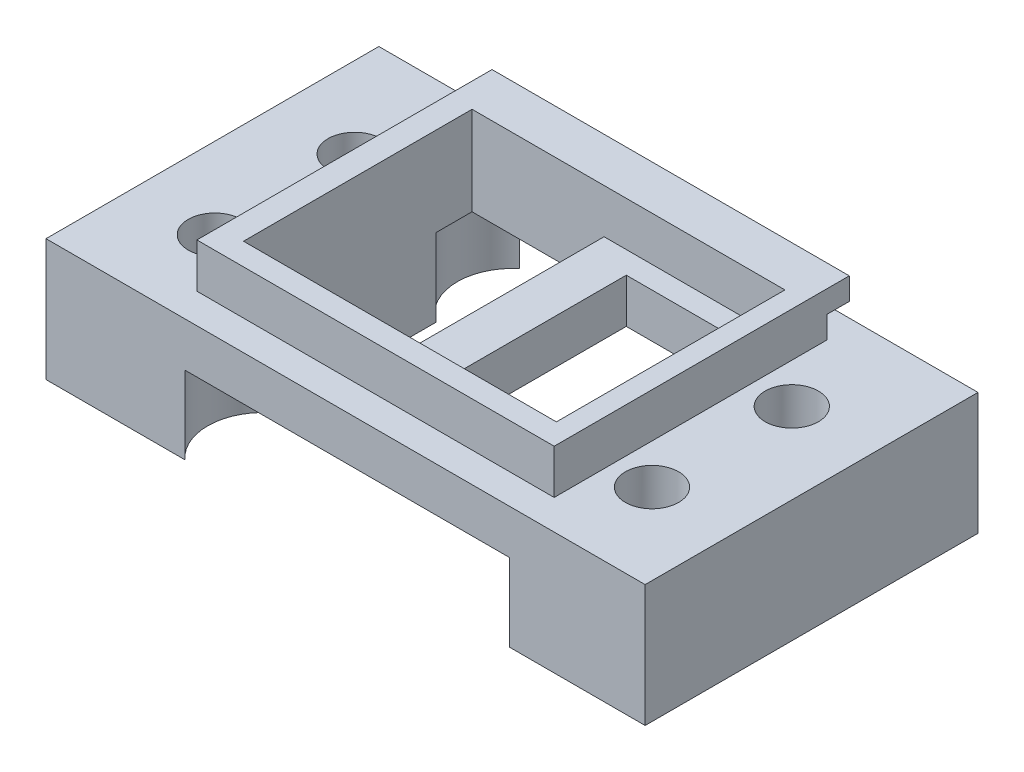
SolidWorks part; units mm, degrees
ref_plane "Front Plane" through (0, 0, 0) normal (0, 0, 1) x (1, 0, 0)
ref_plane "Top Plane" through (0, 0, 0) normal (0, 1, 0) x (1, 0, 0)
ref_plane "Right Plane" through (0, 0, 0) normal (1, 0, 0) x (0, 0, -1)
sketch "Sketch2" plane through (0, 0, 0) normal (0, 1, 0) x (1, 0, 0)
  line L1 (-9.385, 4.8519) -> (10.615, 4.8519)
  line L2 (-9.385, 4.8519) -> (-9.385, -10.1481)
  line L3 (-9.385, -10.1481) -> (10.615, -10.1481)
  line L4 (10.615, 4.8519) -> (10.615, -10.1481)
  dimension "D1" = 20
  dimension "D2" = 15
extrude "Boss-Extrude1" add sketch "Sketch2" along normal blind 2
sketch "Sketch3" plane through (0, 2, 0) normal (0, 1, 0) x (1, 0, 0)
  line L0 (-9.385, 4.8519) -> (-9.385, -10.1481) construction
  line L1 (-6.335, 2.5019) -> (7.765, 2.5019)
  line L2 (-6.335, 2.5019) -> (-6.335, -7.7981)
  line L3 (-6.335, -7.7981) -> (7.765, -7.7981)
  line L4 (7.765, 2.5019) -> (7.765, -7.7981)
  line L5 (-7.435, 3.5019) -> (8.665, 3.5019)
  line L6 (-7.435, 3.5019) -> (-7.435, -8.7981)
  line L7 (-7.435, -8.7981) -> (8.665, -8.7981)
  line L8 (8.665, 3.5019) -> (8.665, -8.7981)
  line L9 (10.615, 4.8519) -> (-9.385, 4.8519) construction
  dimension "D1" = 10.3
  dimension "D2" = 12.3
  dimension "D3" = 14.1
  dimension "D4" = 16.1
  dimension "D5" = 1.95
  dimension "D6" = 3.05
  dimension "D7" = 1.35
  dimension "D8" = 2.35
extrude "Boss-Extrude2" add sketch "Sketch3" along normal blind 2
sketch "Sketch4" plane through (0, 2, 0) normal (0, 1, 0) x (1, 0, 0)
  line L0 (0.615, 4.8519) -> (0.615, -10.1481) construction
  line L1 (10.615, 4.8519) -> (-9.385, 4.8519) construction
  line L2 (-9.385, -10.1481) -> (10.615, -10.1481) construction
  line L3 (-9.385, -2.6481) -> (10.615, -2.6481) construction
  line L4 (-9.385, 4.8519) -> (-9.385, -10.1481) construction
  line L5 (10.615, -10.1481) -> (10.615, 4.8519) construction
  line L6 (-4.385, -6.6602) -> (-4.385, 1.5019) construction
  line L7 (-6.335, -6.7981) -> (-6.335, 2.5019)
  line L8 (-0.385, -6.7981) -> (-0.385, 2.5019)
  line L9 (5.615, -6.6602) -> (5.615, 1.364) construction
  line L12 (7.765, -7.7981) -> (7.765, 1.5019)
  line L13 (1.615, -7.7981) -> (1.615, 1.5019)
  line L14 (-6.335, 2.5019) -> (-0.385, 2.5019)
  line L15 (-6.335, -6.7981) -> (-0.385, -6.7981)
  line L16 (1.615, 1.5019) -> (7.765, 1.5019)
  line L17 (1.615, -7.7981) -> (7.765, -7.7981)
  line L18 (-6.335, 2.5019) -> (-6.335, -7.7981) construction
  line L19 (7.765, -7.7981) -> (7.765, 2.5019) construction
  line L20 (7.765, 2.5019) -> (-6.335, 2.5019) construction
  line L21 (-6.335, -7.7981) -> (7.765, -7.7981) construction
  line L22 (-6.335, -7.7981) -> (7.765, -7.7981) construction
  line L23 (7.765, 2.5019) -> (-6.335, 2.5019) construction
  point P14 (-4.385, -2.6481)
  point P21 (5.615, -2.6481)
  dimension "D1" = 5
  dimension "D2" = 1
  dimension "D3" = 0
  dimension "D4" = 1
  dimension "D5" = 0
  dimension "D6" = 1
  dimension "D7" = 1
  dimension "D8" = 0
  dimension "D9" = 1
  dimension "D10" = 0
extrude "Cut-Extrude1" cut sketch "Sketch4" against normal blind 2
sketch "Sketch5" plane through (0, 2, 0) normal (0, 1, 0) x (1, 0, 0)
  line L1 (-6.335, -6.7981) -> (-6.335, -7.7981) construction
  line L2 (8.665, -8.7981) -> (8.665, 3.5019) construction
  line L3 (-2.36, 2.5019) -> (-2.36, -7.7981) construction
  line L5 (-6.335, -7.7981) -> (1.615, -7.7981) construction
  line L10 (-6.335, -3.4481) -> (8.665, -3.4481) construction
  dimension "D3" = 4.35
sketch "Sketch7" plane through (0, 0, -3.5019) normal (0, 0, -1) x (-1, 0, 0)
  line L0 (7.435, 4) -> (7.435, 2) construction
  line L1 (-8.665, 4) -> (7.435, 4)
  line L2 (-8.665, 4) -> (-8.665, 3)
  line L3 (-8.665, 3) -> (7.435, 3)
  line L4 (7.435, 4) -> (7.435, 3)
  dimension "D1" = 1
extrude "Boss-Extrude3" add sketch "Sketch7" along normal blind 1
sketch "Sketch8" plane through (0, 0, 0) normal (0, -1, 0) x (-1, 0, 0)
  line L0 (9.385, -10.1481) -> (-10.615, -10.1481) construction
  line L1 (0.385, -10.1481) -> (-1.615, -10.1481)
  line L2 (0.385, -10.1481) -> (0.385, 4.8519)
  line L3 (0.385, 4.8519) -> (-1.615, 4.8519)
  line L4 (-1.615, -10.1481) -> (-1.615, 4.8519)
  line L5 (-10.615, 4.8519) -> (9.385, 4.8519) construction
extrude "Boss-Extrude4" add sketch "Sketch8" along normal blind 30
sketch "Sketch9" plane through (1.615, 0, 0) normal (1, 0, 0) x (0, 0, -1)
  line L0 (-2.6481, 0) -> (-2.6481, -30) construction
  line L1 (-10.1481, 0) -> (4.8519, 0) construction
  line L2 (4.8519, -30) -> (-10.1481, -30) construction
  line L3 (-2.6481, -27) -> (-2.6481, -3) construction
  line L6 (-4.4481, -27) -> (-4.4481, -3)
  line L7 (-0.8481, -27) -> (-0.8481, -3)
  arc A2 (-4.4481, -27) -> (-0.8481, -27) centre (-2.6481, -27) ccw
  arc A3 (-0.8481, -3) -> (-4.4481, -3) centre (-2.6481, -3) ccw
  point P8 (-2.6481, -15)
  dimension "D1" = 3
  dimension "D2" = 1.8
extrude "Cut-Extrude2" cut sketch "Sketch9" against normal blind 20
ref_plane "Plane1" through (0, 0, 3.0391) normal (0, 0, -1) x (-1, 0, 0)
sketch "Sketch11" plane through (0, 0, 0) normal (0, -1, 0) x (1, 0, 0)
  line L8 (-0.385, -4.8519) -> (-9.385, -4.8519) construction
  line L9 (-9.385, 10.1481) -> (-12.885, 10.1481)
  line L10 (-9.385, 10.1481) -> (-9.385, -4.8519)
  line L11 (-9.385, -4.8519) -> (-12.885, -4.8519)
  line L12 (-12.885, 10.1481) -> (-12.885, -4.8519)
  line L14 (10.615, 10.1481) -> (14.115, 10.1481)
  line L15 (10.615, 10.1481) -> (10.615, -4.8519)
  line L16 (10.615, -4.8519) -> (14.115, -4.8519)
  line L17 (14.115, 10.1481) -> (14.115, -4.8519)
  line L18 (10.615, -4.8519) -> (1.615, -4.8519) construction
  dimension "D1" = 3.5
  dimension "D2" = 0
  dimension "D3" = 3.5
  dimension "D4" = 0
extrude "Boss-Extrude5" add sketch "Sketch11" along normal blind 5.5 from surface at -2 starting at face at (0.615, 2, 2.6481)
sketch "Sketch10" plane through (0, 2, 0) normal (0, 1, 0) x (1, 0, 0)
  line L0 (0.615, 4.344) -> (0.615, -8.956) construction
  line L1 (0.615, 4.5019) -> (0.615, -10.1481) construction
  line L2 (-7.435, 4.5019) -> (8.665, 4.5019) construction
  line L3 (-12.885, -10.1481) -> (14.115, -10.1481) construction
  line L5 (2.2, -3.0391) -> (-2.2, -3.0391) construction
  circle A0 centre (10.465, -6.1891) radius 1.2
  circle A1 centre (10.465, 0.1109) radius 1.2
  circle A2 centre (-9.235, 0.1109) radius 1.2
  circle A3 centre (-9.235, -6.1891) radius 1.2
  dimension "D5" = 2.4
  dimension "2.4" = 2.4
  dimension "D1" = 6.3
  dimension "D2" = 19.7
  dimension "D3" = 3.15
  dimension "D4" = 9.85
extrude "Cut-Extrude3" cut sketch "Sketch10" against normal through all both
sketch "Sketch12" plane through (0, 0, 0) normal (0, -1, 0) x (1, 0, 0)
  line L0 (-0.385, -4.8519) -> (-9.385, -4.8519) construction
  line L1 (-9.385, 10.1481) -> (-6.335, 10.1481)
  line L2 (-9.385, 10.1481) -> (-9.385, 7.3797)
  line L3 (-9.385, -4.8519) -> (-6.335, -4.8519)
  line L4 (-6.335, 10.1481) -> (-6.335, -4.8519)
  line L5 (10.615, -4.8519) -> (1.615, -4.8519) construction
  line L6 (10.615, 10.1481) -> (7.765, 10.1481)
  line L7 (10.615, 10.1481) -> (10.615, 7.3797)
  line L8 (10.615, -4.8519) -> (7.765, -4.8519)
  line L9 (7.765, 10.1481) -> (7.765, -4.8519)
  line L10 (-9.385, 4.9985) -> (-9.385, 1.0797)
  line L11 (-9.385, -1.3015) -> (-9.385, -4.8519)
  line L12 (10.615, -1.3015) -> (10.615, -4.8519)
  line L13 (10.615, 4.9985) -> (10.615, 1.0797)
  line L14 (10.615, 4.9985) -> (10.615, 1.0797) construction
  line L15 (10.615, 1.0797) -> (10.615, 4.9985) construction
  arc A0 (-9.385, 4.9985) -> (-9.385, 7.3797) centre (-9.1979, 6.1891) ccw
  arc A1 (-9.385, -1.3015) -> (-9.385, 1.0797) centre (-9.1763, -0.1109) ccw
  arc A2 (10.615, 7.3797) -> (10.615, 4.9985) centre (10.4496, 6.1891) ccw
  arc A3 (10.615, 1.0797) -> (10.615, -1.3015) centre (10.4437, -0.1109) ccw
extrude "Boss-Extrude6" add sketch "Sketch12" along normal up to vertex
sketch "Sketch13" plane through (0, 0, -4.5019) normal (0, 0, -1) x (-1, 0, 0)
  line L0 (6.745, 3.8045) -> (6.745, 3.3025)
  line L1 (6.745, 3.3025) -> (6.745, 3.0955) construction
  arc A0 (6.745, 3.8045) -> (6.745, 3.3025) centre (6.745, 3.5535) cw
revolve "Cut-Revolve1" cut sketch "Sketch13" angle 360 about L1
sketch "Sketch14" plane through (0, -30, 0) normal (0, -1, 0) x (1, 0, 0)
  line L1 (-0.385, 10.1481) -> (1.615, 10.1481)
  line L2 (-0.385, 10.1481) -> (-0.385, -4.8519)
  line L3 (-0.385, -4.8519) -> (1.615, -4.8519)
  line L4 (1.615, 10.1481) -> (1.615, -4.8519)
extrude "Cut-Extrude4" cut sketch "Sketch14" against normal up to vertex
sketch "Sketch15" plane through (0, -3.5, 0) normal (0, -1, 0) x (1, 0, 0)
  line L0 (0.7184, 10.152) -> (0.7184, -4.848) construction
  circle A4 centre (-4.9366, 8.307) radius 2.5
  circle A5 centre (6.3134, 8.307) radius 2.5
  circle A6 centre (6.3134, -2.943) radius 2.5
  circle A7 centre (-4.9366, -2.943) radius 2.5
  dimension "D2" = 2
  dimension "D1" = 2
extrude "Cut-Extrude5" cut sketch "Sketch15" against normal up to surface (3.5 mm away) up to face at (0.6817, 0, 2.6481)
